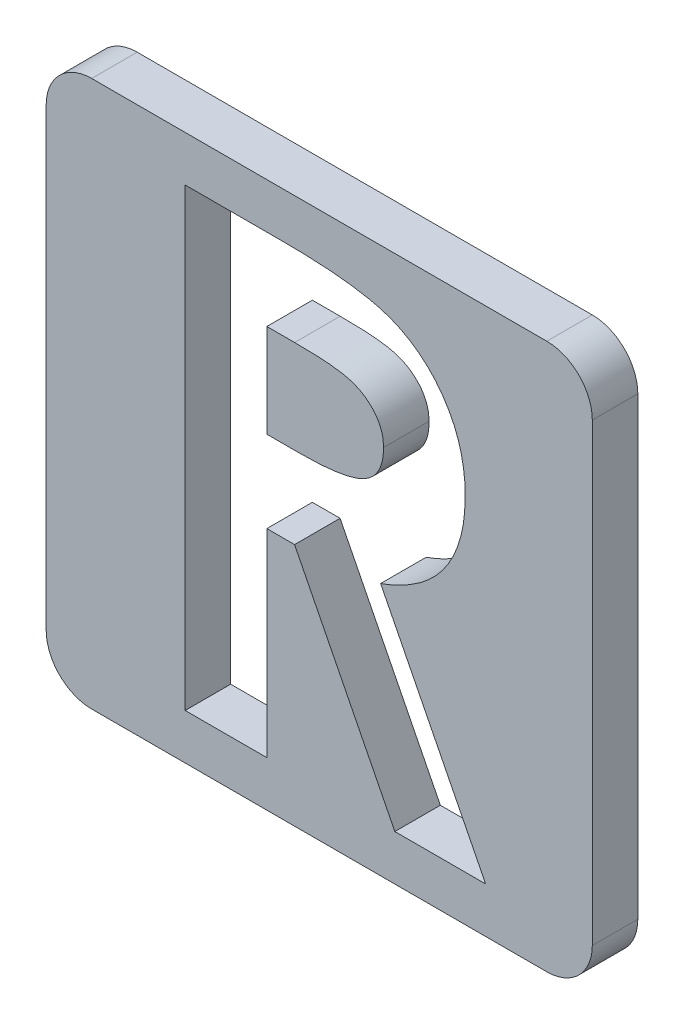
SolidWorks part; units mm, degrees
ref_plane "Front Plane" through (0, 0, 0) normal (0, 0, 1) x (1, 0, 0)
ref_plane "Top Plane" through (0, 0, 0) normal (0, 1, 0) x (1, 0, 0)
ref_plane "Right Plane" through (0, 0, 0) normal (1, 0, 0) x (0, 0, -1)
sketch "Sketch1" plane through (0, 0, 0) normal (0, 0, 1) x (1, 0, 0)
  line L1 (-50, 60) -> (50, 60)
  line L2 (-60, 50) -> (-60, -50)
  line L3 (-50, -60) -> (50, -60)
  line L4 (60, 50) -> (60, -50)
  line L5 (-60, 60) -> (60, -60) construction
  line L6 (-60, -60) -> (60, 60) construction
  arc A0 (-60, -50) -> (-50, -60) centre (-50, -50) ccw
  arc A1 (50, -60) -> (60, -50) centre (50, -50) ccw
  arc A2 (50, 60) -> (60, 50) centre (50, 50) cw
  arc A3 (-50, 60) -> (-60, 50) centre (-50, 50) ccw
  point P0 (0, 0)
  dimension "D3" = 10
  dimension "D1" = 120
  dimension "D2" = 120
extrude "Boss-Extrude1" add sketch "Sketch1" along normal blind 10 contours A3 L2 A0 L3 A1 L4 A2 L1
sketch "Sketch2" plane through (0, 0, 10) normal (0, 0, 1) x (1, 0, 0)
  line L0 (0, 0) -> (0, 40) construction
  line L1 (-50, 50) -> (50, 50) construction
  line L2 (-50, 50) -> (-50, -50) construction
  line L3 (-50, -50) -> (50, -50) construction
  line L4 (50, 50) -> (50, -50) construction
  line L5 (-50, 50) -> (50, -50) construction
  line L6 (-50, -50) -> (50, 50) construction
  line L7 (0, 40) -> (-40, 40) construction
  line L8 (-40, 40) -> (-40, 0) construction
  line L9 (-40, 0) -> (0, 0) construction
  line L11 (0, 20) -> (-20, 20) construction
  line L12 (-20, 40) -> (-20, 20) construction
  circle A0 centre (0, 40) radius 4 construction
  circle A1 centre (0, 20) radius 4 construction
  circle A2 centre (0, 0) radius 4 construction
  circle A3 centre (-20, 20) radius 4 construction
  circle A4 centre (-20, 40) radius 4 construction
  circle A5 centre (-40, 40) radius 4 construction
  circle A6 centre (0, 0) radius 4 construction
  circle A7 centre (20, 0) radius 4 construction
  circle A8 centre (40, 0) radius 4 construction
  circle A9 centre (40, 20) radius 4 construction
  circle A10 centre (40, 40) radius 4 construction
  circle A11 centre (20, 20) radius 4 construction
  circle A12 centre (0, 0) radius 4 construction
  circle A13 centre (0, -20) radius 4 construction
  circle A14 centre (0, -40) radius 4 construction
  circle A15 centre (20, -40) radius 4 construction
  circle A16 centre (40, -40) radius 4 construction
  circle A17 centre (20, -20) radius 4 construction
  circle A18 centre (0, 0) radius 4 construction
  circle A19 centre (-20, 0) radius 4 construction
  circle A20 centre (-40, 0) radius 4 construction
  circle A21 centre (-40, -20) radius 4 construction
  circle A22 centre (-40, -40) radius 4 construction
  circle A23 centre (-20, -20) radius 4 construction
  text T0 "R" font "Century Gothic" height 100
  point P0 (0, 0)
  point P55 (0, 0)
  dimension "D4" = 8
  dimension "D1" = 100
  dimension "D2" = 100
  dimension "D3" = 40
  dimension "D5" = 4
extrude "Cut-Extrude31" cut sketch "Sketch2" against normal blind 10
